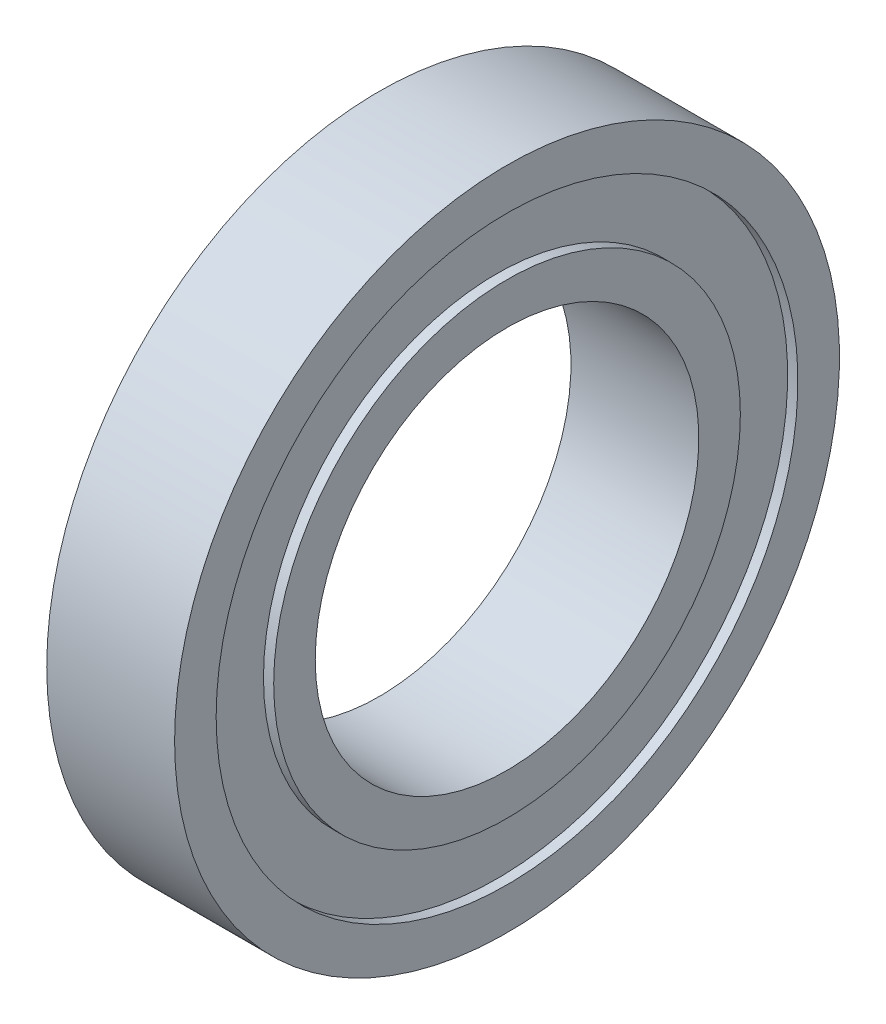
SolidWorks part; units mm, degrees
ref_plane "Front Plane" through (0, 0, 0) normal (0, 0, 1) x (1, 0, 0)
ref_plane "Top Plane" through (0, 0, 0) normal (0, 1, 0) x (1, 0, 0)
ref_plane "Right Plane" through (0, 0, 0) normal (1, 0, 0) x (0, 0, -1)
sketch "Sketch1" plane through (0, 0, 0) normal (0, 1, 0) x (1, 0, 0)
  line L0 (0, 7.5) -> (0, 9.125)
  line L1 (0, 9.125) -> (0.4, 9.125)
  line L2 (0.4, 9.125) -> (0.4, 11.375)
  line L3 (0.4, 11.375) -> (0, 11.375)
  line L4 (0, 11.375) -> (0, 13)
  line L5 (0, 13) -> (5, 13)
  line L6 (5, 13) -> (5, 11.375)
  line L7 (5, 11.375) -> (4.6, 11.375)
  line L8 (4.6, 11.375) -> (4.6, 9.125)
  line L9 (4.6, 9.125) -> (5, 9.125)
  line L10 (5, 9.125) -> (5, 7.5)
  line L11 (5, 7.5) -> (0, 7.5)
  line L12 (0, 0) -> (6.9499, 0) construction
  dimension "D1" = 7.5
  dimension "D2" = 13
  dimension "D3" = 2.25
  dimension "D5" = 5
  dimension "D6" = 0.4
revolve "Revolve1" add sketch "Sketch1" angle 360 about L12
